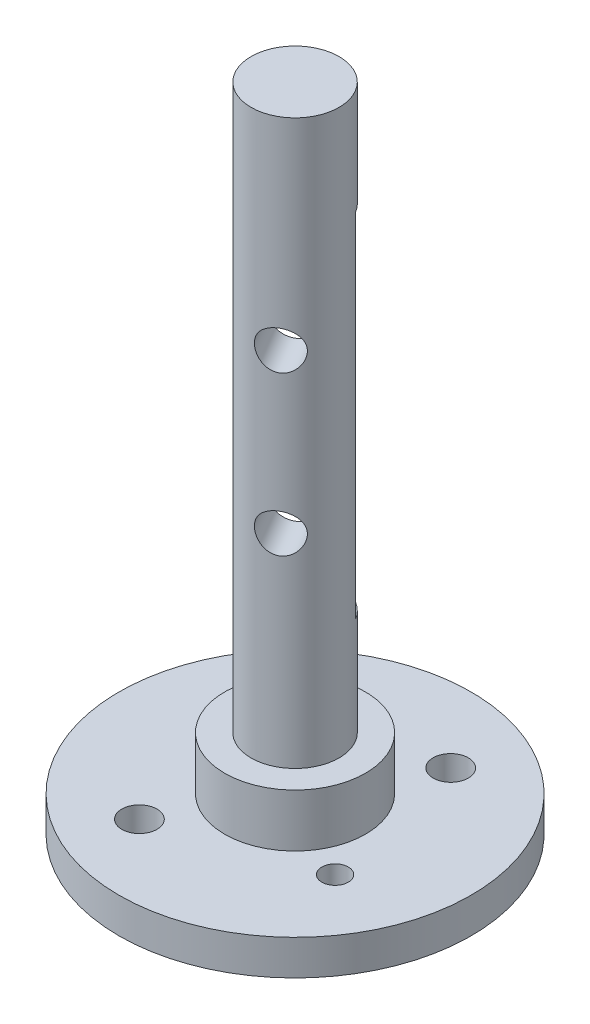
SolidWorks part; units mm, degrees
ref_plane "前视基准面" through (0, 0, 0) normal (0, 0, 1) x (1, 0, 0)
ref_plane "上视基准面" through (0, 0, 0) normal (0, 1, 0) x (1, 0, 0)
ref_plane "右视基准面" through (0, 0, 0) normal (1, 0, 0) x (0, 0, -1)
sketch "草图1" plane through (0, 0, 0) normal (0, 1, 0) x (1, 0, 0)
  circle A0 centre (0, 0) radius 10
extrude "凸台-拉伸1" add sketch "草图1" along normal blind 2
sketch "草图2" plane through (0, 2, 0) normal (0, 1, 0) x (1, 0, 0)
  circle A0 centre (0, 0) radius 2.5
extrude "凸台-拉伸2" add sketch "草图2" along normal blind 35
sketch "草图3" plane through (0, 0, 0) normal (0, -1, 0) x (1, 0, 0)
  circle A1 centre (-3.1593, 5.6806) radius 1
  circle A2 centre (3.1593, -5.6806) radius 1
  circle A3 centre (5.1213, 2.8482) radius 0.75
  circle A4 centre (-5.1213, -2.8482) radius 0.75
extrude "切除-拉伸1" cut sketch "草图3" against normal blind 3
sketch "草图4" plane through (0, 0, 0) normal (0, -1, 0) x (1, 0, 0)
  circle A0 centre (0, 0) radius 3.5
extrude "切除-拉伸2" cut sketch "草图4" against normal blind 1
sketch "草图6" plane through (0, 2, 0) normal (0, 1, 0) x (1, 0, 0)
  circle A0 centre (0, 0) radius 4
extrude "凸台-拉伸4" add sketch "草图6" along normal blind 3
sketch "草图7" plane through (0, 37, 0) normal (0, 1, 0) x (1, 0, 0)
  line L0 (2.1577, 1.2626) -> (-2.1577, -1.2626)
  arc A0 (2.1577, 1.2626) -> (-2.1577, -1.2626) centre (0, 0) ccw
  circle A1 centre (0, 0) radius 2.5 construction
extrude "切除-拉伸3" cut sketch "草图7" against normal blind 20 from offset 6 offset against normal yes
ref_point "点2"
sketch "草图12" plane through (0, 0, 0) normal (-0.505, 0, -0.8631) x (-0.8631, 0, 0.505)
  line L0 (0, 21) -> (0, 16.5)
  circle A0 centre (0, 16.5) radius 1.1
extrude "切除-拉伸6" cut sketch "草图12" against normal blind 3
ref_plane "基准面1" through (0, 21, 0) normal (0, 1, 0) x (1, 0, 0)
mirror "镜向1" about plane through (0, 21, 0) normal (0, 1, 0) of "切除-拉伸6"
